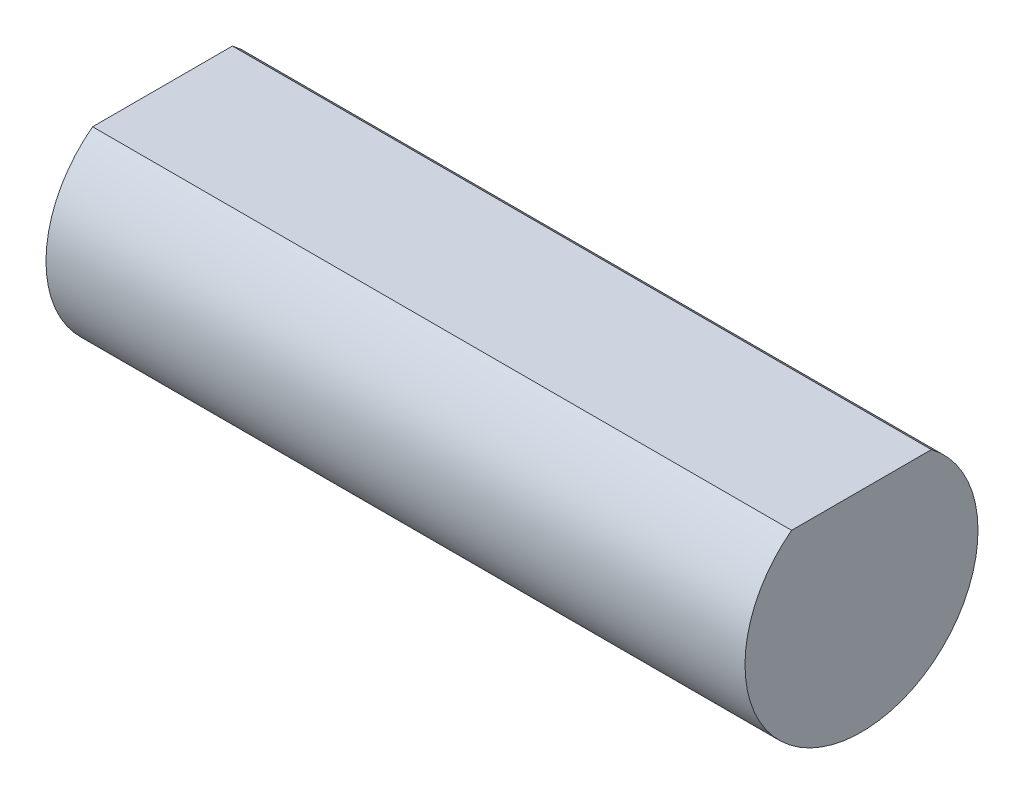
SolidWorks part; units mm, degrees
ref_plane "Front Plane" through (0, 0, 0) normal (0, 0, 1) x (1, 0, 0)
ref_plane "Top Plane" through (0, 0, 0) normal (0, 1, 0) x (1, 0, 0)
ref_plane "Right Plane" through (0, 0, 0) normal (1, 0, 0) x (0, 0, -1)
sketch "Sketch1" plane through (0, 0, 0) normal (1, 0, 0) x (0, 0, -1)
  line L0 (-1.905, 2.54) -> (1.905, 2.54)
  line L1 (0, 2.54) -> (0, 0) construction
  circle A0 centre (0, 0) radius 3.175
  dimension "D1" = 6.35
  dimension "D2" = 2.54
extrude "Boss-Extrude1" add sketch "Sketch1" along normal blind 19.05
